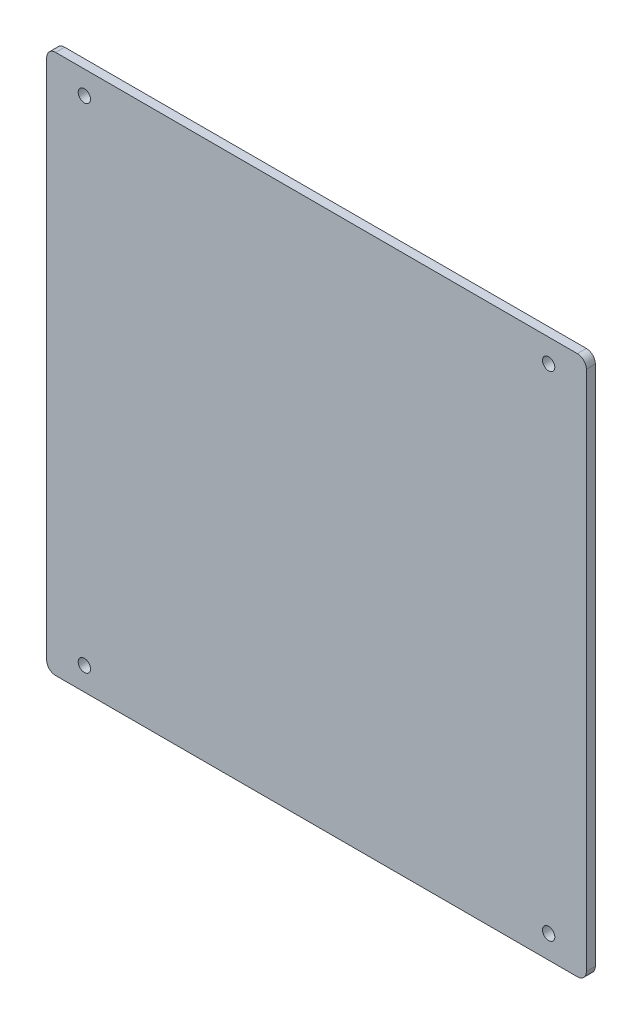
SolidWorks part; units mm, degrees
material "Thornel Mat VMA"
ref_plane "Front Plane" through (0, 0, 0) normal (0, 0, 1) x (1, 0, 0)
ref_plane "Top Plane" through (0, 0, 0) normal (0, 1, 0) x (1, 0, 0)
ref_plane "Right Plane" through (0, 0, 0) normal (1, 0, 0) x (0, 0, -1)
sketch "Sketch1" plane through (0, 0, 0) normal (0, 0, 1) x (1, 0, 0)
  line L1 (-90, -90) -> (90, -90)
  line L2 (-90, -90) -> (-90, 90)
  line L3 (-90, 90) -> (90, 90)
  line L4 (90, -90) -> (90, 90)
  line L5 (-90, -90) -> (90, 90) construction
  line L6 (-90, 90) -> (90, -90) construction
  point P0 (0, 0)
  dimension "D1" = 180
  dimension "D2" = 180
extrude "Boss-Extrude1" add sketch "Sketch1" along normal blind 3
fillet "Fillet1" radius 3 4 edges at (90, -90, 1.5) (-90, -90, 1.5) (-90, 90, 1.5) (90, 90, 1.5)
sketch "草图1" plane through (0, 0, 3) normal (0, 0, 1) x (1, 0, 0)
  line L0 (0, 0) -> (0, 18.9642) construction
  line L1 (-77.4295, -82.2688) -> (77.4295, -82.2688) construction
  line L2 (-77.4295, -82.2688) -> (-77.4295, 82.2688) construction
  line L3 (-77.4295, 82.2688) -> (77.4295, 82.2688) construction
  line L4 (77.4295, -82.2688) -> (77.4295, 82.2688) construction
  line L5 (-77.4295, -82.2688) -> (77.4295, 82.2688) construction
  line L6 (-77.4295, 82.2688) -> (77.4295, -82.2688) construction
  line L7 (0, 0) -> (17.4804, 0) construction
  circle A0 centre (-77.4295, 82.2688) radius 2.05
  circle A1 centre (77.4295, 82.2688) radius 2.05
  circle A2 centre (77.4295, -82.2688) radius 2.05
  circle A3 centre (-77.4295, -82.2688) radius 2.05
  point P0 (0, 0)
  point P1 (0, 0)
  dimension "D3" = 4.1
  dimension "D1" = 154.859
  dimension "D2" = 164.5377
extrude "切除-拉伸1" cut sketch "草图1" against normal up to next
